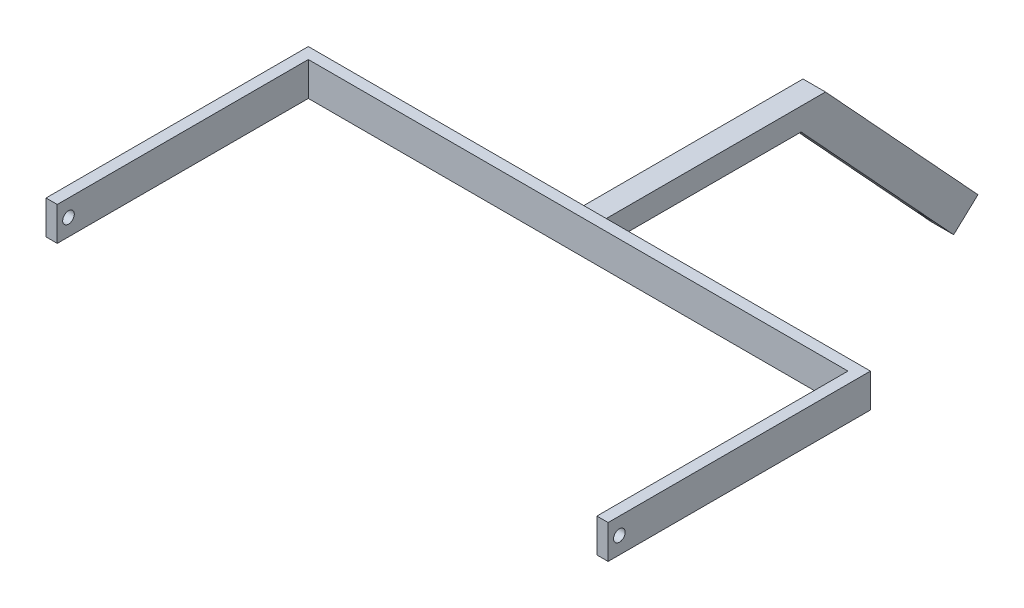
SolidWorks part; units mm, degrees
ref_plane "前视基准面" through (0, 0, 0) normal (0, 0, 1) x (1, 0, 0)
ref_plane "上视基准面" through (0, 0, 0) normal (0, 1, 0) x (1, 0, 0)
ref_plane "右视基准面" through (0, 0, 0) normal (1, 0, 0) x (0, 0, -1)
other "Configuration Table"
sketch "草图1" plane through (0, 0, 0) normal (0, 1, 0) x (1, 0, 0)
  line L0 (-72.7576, -1.4848) -> (-72.7576, -68.4848)
  line L1 (71.2424, -1.4848) -> (-72.7576, -1.4848)
  line L2 (74.2424, -1.4848) -> (74.2424, 1.5152)
  line L3 (74.2424, 1.5152) -> (-75.7576, 1.5152)
  line L4 (-75.7576, -1.4848) -> (-75.7576, 1.5152)
  line L5 (71.2424, -1.4248) -> (-75.7576, 1.5152) construction
  line L6 (74.2424, 1.5152) -> (-72.7576, -1.4848) construction
  line L7 (-75.7576, 1.5152) -> (-72.7576, 1.5152)
  line L8 (-75.7576, 1.5152) -> (-75.7576, -68.4848)
  line L9 (-75.7576, -68.4848) -> (-72.7576, -68.4848)
  line L10 (-72.7576, 1.5152) -> (-72.7576, 1.4552)
  line L11 (74.2424, 1.5152) -> (71.2424, 1.5152)
  line L12 (74.2424, 1.5152) -> (74.2424, -68.4848)
  line L13 (74.2424, -68.4848) -> (71.2424, -68.4848)
  line L14 (71.2424, 1.5152) -> (71.2424, 1.4539)
  line L15 (71.2424, -1.4248) -> (71.2424, -68.4848)
  point P0 (0, 0)
  point P12 (-72.7576, -1.4848)
  point P13 (71.2424, -1.4848)
  dimension "D1" = 150
  dimension "D2" = 3
  dimension "D3" = 3
  dimension "D4" = 70
  dimension "D5" = 70
  dimension "D6" = 3
  dimension "D7" = 67
  dimension "D8" = 67.06
  dimension "D9" = 150
  dimension "D10" = 67
extrude "凸台-拉伸2" add sketch "草图1" along normal blind 6
sketch "草图2" plane through (-72.7576, 0, 0) normal (1, 0, 0) x (0, 0, -1)
  line L0 (-68.4848, 6) -> (-68.4848, 0) construction
  line L1 (-1.4848, 0) -> (-68.4848, 0) construction
  circle A0 centre (-65.4848, 3) radius 1.55
  dimension "D2" = 3.1
  dimension "D1" = 3
  dimension "D3" = 3
extrude "切除-拉伸1" cut sketch "草图2" against normal blind 10
sketch "草图3" plane through (74.2424, 0, 0) normal (1, 0, 0) x (0, 0, -1)
  line L0 (-68.4848, 6) -> (-68.4848, 0) construction
  line L1 (1.5152, 0) -> (-68.4848, 0) construction
  circle A0 centre (-65.4848, 3) radius 1.55
  dimension "D2" = 3.1
  dimension "D1" = 3
  dimension "D3" = 3
extrude "切除-拉伸2" cut sketch "草图3" against normal blind 10 contours A0
sketch "草图5" plane through (0, 0, -1.5152) normal (0, 0, -1) x (-1, 0, 0)
  line L3 (3.7576, 0) -> (-2.2424, 0)
  line L4 (3.7576, 0) -> (3.7576, 6)
  line L5 (3.7576, 6) -> (-2.2424, 6)
  line L6 (-2.2424, 0) -> (-2.2424, 6)
  line L7 (3.7576, 0) -> (-2.2424, 6) construction
  line L8 (3.7576, 6) -> (-2.2424, 0) construction
  line L9 (75.7576, 6) -> (75.7576, 0) construction
  line L12 (-74.2424, 0) -> (75.7576, 0) construction
  point P0 (0.7576, 3)
  point P9 (-119.8597, 50.5531)
  dimension "D3" = 6
  dimension "D1" = 75
  dimension "D2" = 3
  dimension "D4" = 6
sketch "草图6" plane through (0, 6, 0) normal (0, 1, 0) x (1, 0, 0)
  line L0 (-75.7576, 1.5152) -> (74.2424, 1.5152)
  line L1 (74.2424, 1.5152) -> (74.2424, -68.4848)
  line L2 (74.2424, -68.4848) -> (71.2424, -68.4848)
  line L3 (71.2424, -68.4848) -> (71.2424, -1.4848)
  line L4 (71.2424, -1.4848) -> (-72.7576, -1.4848)
  line L5 (-72.7576, -1.4848) -> (-72.7576, -68.4848)
  line L6 (-72.7576, -68.4848) -> (-75.7576, -68.4848)
  line L7 (-75.7576, -68.4848) -> (-75.7576, 1.5152)
extrude "凸台-拉伸4" add sketch "草图6" along normal blind 1.5
sketch "草图7" plane through (0, 0, 0) normal (0, -1, 0) x (1, 0, 0)
  line L0 (-75.7576, 68.4848) -> (-75.7576, -1.5152)
  line L1 (-75.7576, -1.5152) -> (74.2424, -1.5152)
  line L2 (74.2424, -1.5152) -> (74.2424, 68.4848)
  line L3 (74.2424, 68.4848) -> (71.2424, 68.4848)
  line L4 (71.2424, 68.4848) -> (71.2424, 1.4848)
  line L5 (71.2424, 1.4848) -> (-72.7576, 1.4848)
  line L6 (-72.7576, 1.4848) -> (-72.7576, 68.4848)
  line L7 (-72.7576, 68.4848) -> (-75.7576, 68.4848)
extrude "凸台-拉伸5" add sketch "草图7" along normal blind 1.5
extrude "凸台-拉伸6" add sketch "草图5" along normal blind 60 contours L5 L6 L3 L4
sketch "草图8" plane through (2.2424, 0, 0) normal (1, 0, 0) x (0, 0, -1)
  line L0 (61.5152, 6) -> (55.0152, 0)
  line L1 (61.5152, 0) -> (1.5152, 0) construction
  line L2 (55.0152, 0) -> (61.5152, 0)
  line L3 (61.5152, 0) -> (61.5152, 6)
  dimension "D1" = 6.5
extrude "切除-拉伸3" cut sketch "草图8" against normal blind 60
sketch "草图9" plane through (0, -27.4197, -25.3105) normal (0, -0.7348, -0.6783) x (1, 0, 0)
  line L0 (-3.7576, -40.4253) -> (-3.7576, -49.2712)
  line L1 (-3.7576, -49.2712) -> (2.2424, -49.2712)
  line L2 (2.2424, -49.2712) -> (2.2424, -40.4253)
  line L3 (2.2424, -40.4253) -> (-3.7576, -40.4253)
extrude "凸台-拉伸7" add sketch "草图9" along normal blind 60
sketch "草图10" plane through (0, -71.5079, -66.0073) normal (0, -0.7348, -0.6783) x (1, 0, 0)
  line L0 (-3.7576, -40.4253) -> (2.2424, -49.2712) construction
  line L1 (-3.7576, -49.2712) -> (2.2424, -40.4253) construction
  line L3 (1.7424, -45.8483) -> (-3.2576, -45.8483)
  line L4 (1.7424, -45.8483) -> (1.7424, -43.8483)
  line L5 (1.7424, -43.8483) -> (-3.2576, -43.8483)
  line L6 (-3.2576, -45.8483) -> (-3.2576, -43.8483)
  line L7 (1.7424, -45.8483) -> (-3.2576, -43.8483) construction
  line L8 (1.7424, -43.8483) -> (-3.2576, -45.8483) construction
  point P8 (-0.7576, -44.8483)
  point P9 (-0.7576, -44.8483)
  dimension "D1" = 2
  dimension "D2" = 5
extrude "切除-拉伸4" cut sketch "草图10" against normal blind 10
sketch "草图11" plane through (0, 33.4197, -36.2047) normal (0, 0.6783, -0.7348) x (-1, 0, 0)
  line L0 (-2.2424, -97.3157) -> (-2.2424, -37.3157) construction
  line L1 (3.7576, -97.3157) -> (-2.2424, -97.3157)
  line L2 (3.7576, -97.3157) -> (3.7576, -87.3157)
  line L3 (3.7576, -87.3157) -> (-2.2424, -87.3157)
  line L4 (-2.2424, -97.3157) -> (-2.2424, -87.3157)
  circle A0 centre (0.7576, -90.3157) radius 1.55
  dimension "D4" = 3.1
  dimension "D1" = 10
  dimension "D2" = 3
  dimension "D3" = 3
extrude "切除-拉伸5" cut sketch "草图11" against normal blind 10 contours A0
